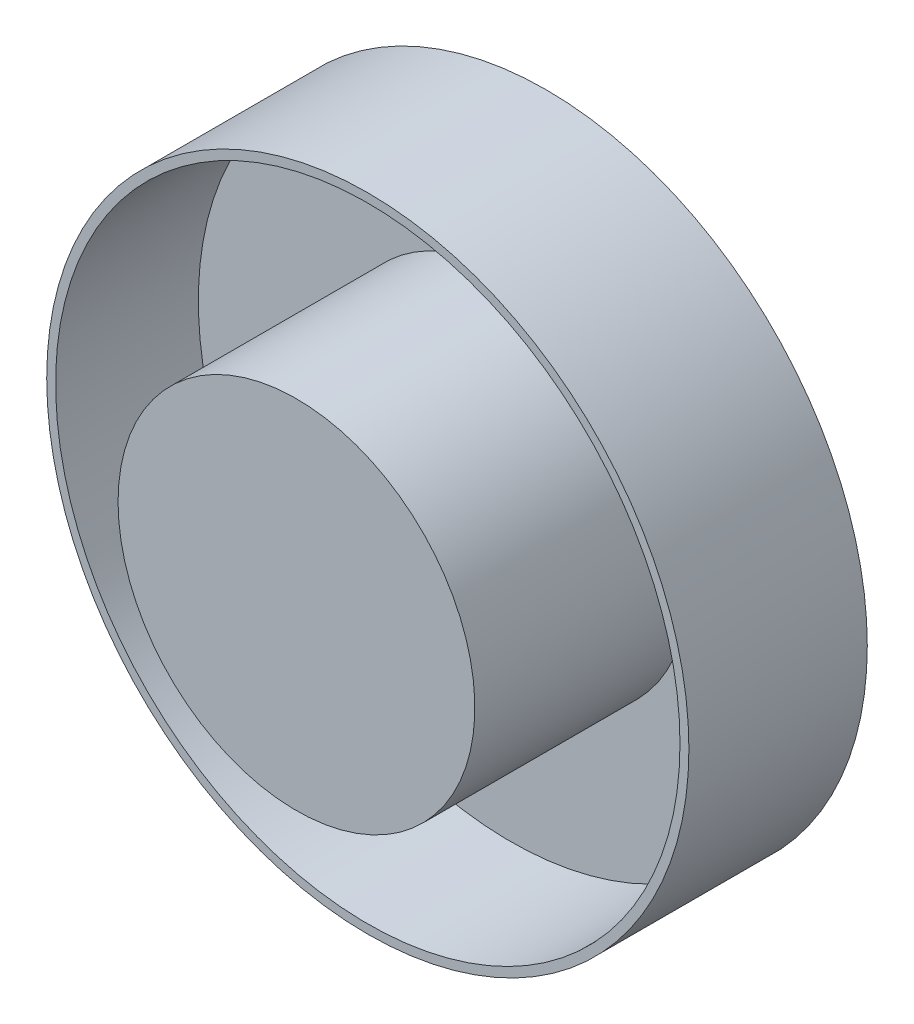
SolidWorks part; units mm, degrees
material "Polyethylene Cross-Linked"
ref_plane "X-Y Datum" through (0, 0, 0) normal (0, 0, 1) x (1, 0, 0)
ref_plane "X-Z Datum" through (0, 0, 0) normal (0, 1, 0) x (1, 0, 0)
ref_plane "Y-Z Datum" through (0, 0, 0) normal (1, 0, 0) x (0, 0, -1)
sketch "Sketch1" plane through (0, 0, 0) normal (0, 0, 1) x (1, 0, 0)
  circle A0 centre (0, 0) radius 22.86
  dimension "D1" = 45.72
extrude "Boss-Extrude1" add sketch "Sketch1" along normal blind 12.7
sketch "Sketch2" plane through (0, 0, 12.7) normal (0, 0, 1) x (1, 0, 0)
  circle A0 centre (0, 0) radius 22.225
  dimension "D1" = 44.45
extrude "Cut-Extrude1" cut sketch "Sketch2" against normal blind 10.16
sketch "Sketch3" plane through (0, 0, 2.54) normal (0, 0, 1) x (1, 0, 0)
  circle A0 centre (0, 0) radius 12.7
  dimension "D1" = 25.4
extrude "Boss-Extrude2" add sketch "Sketch3" along normal blind 15.24
